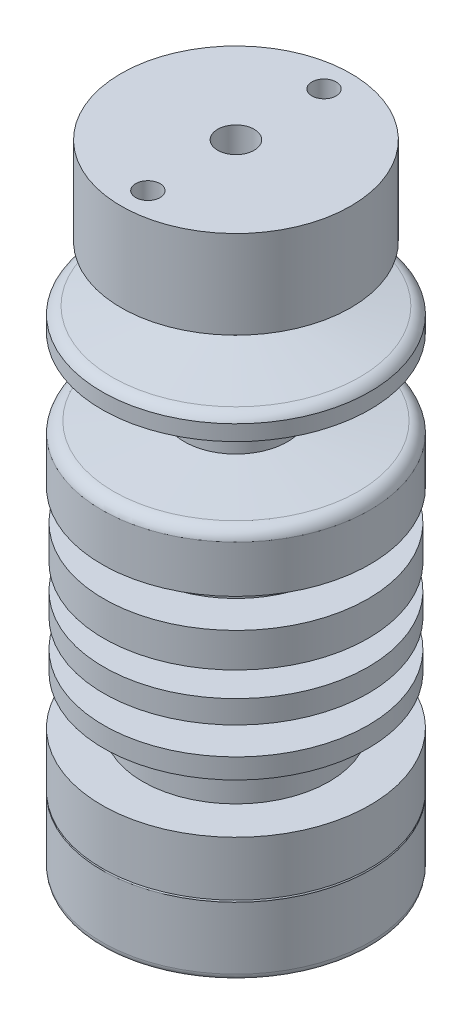
SolidWorks part; units mm, degrees
ref_plane "Alzado" through (0, 0, 0) normal (0, 0, 1) x (1, 0, 0)
ref_plane "Planta" through (0, 0, 0) normal (0, 1, 0) x (1, 0, 0)
ref_plane "Vista lateral" through (0, 0, 0) normal (1, 0, 0) x (0, 0, -1)
sketch "Croquis1" plane through (0, 0, 0) normal (0, 0, 1) x (1, 0, 0)
  line L0 (0, 0) -> (0, 43.0446) construction
  line L1 (0, 43.0446) -> (0, -121.9554) construction
  line L2 (0, 43.0446) -> (30, 43.0446)
  line L3 (30, 43.0446) -> (30, 20.0446)
  line L4 (30, 20.0446) -> (12.9858, 20.0446)
  line L5 (12.9858, 20.0446) -> (12.9858, 10.4062)
  line L6 (13.718, 8.5125) -> (32.3097, 5.486)
  line L7 (35, 3.5416) -> (35, -0.4901)
  line L8 (13.4687, -0.4901) -> (35, -0.4901)
  line L9 (13.4687, -0.4901) -> (13.4687, -18.5388)
  line L10 (13.4687, -18.5388) -> (31.9792, -20.5132)
  line L11 (35, -23.2242) -> (35, -35.5011)
  line L12 (24.3347, -77.3577) -> (34.5383, -77.3577)
  line L13 (24.3347, -77.3577) -> (24.3347, -104.2217)
  line L14 (24.3347, -104.2217) -> (34.5383, -104.2217)
  line L15 (35, -104.6833) -> (35, -120.9509)
  line L16 (34.7378, -121.991) -> (0, -121.9554)
  line L17 (0, 43.0446) -> (0, -121.9554)
  line L18 (34.5383, -77.3577) -> (34.5383, -72.1328)
  line L19 (35, -35.5011) -> (24.3347, -35.5011)
  line L20 (24.3347, -35.5011) -> (24.3347, -43.5201)
  line L21 (34.5383, -72.1328) -> (24.3347, -72.1328)
  line L22 (24.3347, -64.9174) -> (34.5383, -64.9174)
  line L23 (34.5383, -64.9174) -> (34.5383, -58.9461)
  line L24 (34.5383, -58.9461) -> (24.3347, -58.9461)
  line L25 (24.3347, -52.4771) -> (34.5383, -52.4771)
  line L26 (34.5383, -52.4771) -> (34.5383, -43.5201)
  line L27 (34.5383, -43.5201) -> (24.3347, -43.5201)
  line L28 (24.3347, -64.9174) -> (24.3347, -72.1328)
  line L29 (24.3347, -52.4771) -> (24.3347, -58.9461)
  arc A2 (12.9858, 10.4062) -> (13.718, 8.5125) centre (15.8008, 10.4062) ccw
  arc A3 (32.3097, 5.486) -> (35, 3.5416) centre (31.7144, 1.829) cw
  arc A6 (31.9792, -20.5132) -> (35, -23.2242) centre (31.6114, -23.9615) cw
  arc A8 (34.5383, -104.2217) -> (35, -104.6833) centre (34.5383, -104.6833) cw
  arc A9 (35, -120.9509) -> (34.7378, -121.991) centre (32.8058, -120.9509) cw
  dimension "D1" = 165
  dimension "D2" = 23
  dimension "D3" = 35
  dimension "D4" = 35
  dimension "D5" = 35
revolve "Revolución3" add sketch "Croquis1" angle 360 about L17
sketch "Croquis5" plane through (0, -104.2217, 0) normal (0, 1, 0) x (1, 0, 0)
  circle A0 centre (0.0979, 0) radius 7.9375
  dimension "D1" = 15.875
extrude "Cortar-Extruir3" cut sketch "Croquis5" along normal blind 8 and the other way blind 27
ref_plane "Plano1" through (0, 0, 0) normal (1, 0, 0) x (0, 0, -1)
ref_plane "Plano2" through (0, 0, 0) normal (0, 0, 1) x (1, 0, 0)
sketch "Croquis9" plane through (0, 43.0446, 0) normal (0, 1, 0) x (1, 0, 0)
  line L0 (0, 0) -> (0, -23) construction
  line L1 (0, -38.5) -> (0, 38.5) construction
  line L2 (0, 0) -> (0, 23) construction
  circle A0 centre (0, 23) radius 3.175
  circle A1 centre (0, -23) radius 3.175
  dimension "D3" = 6.35
  dimension "D4" = 6.35
  dimension "D1" = 23
  dimension "D2" = 23
extrude "Cortar-Extruir5" cut sketch "Croquis9" against normal blind 18
sketch "Croquis10" plane through (0, 43.0446, 0) normal (0, 1, 0) x (1, 0, 0)
  circle A0 centre (0, 0) radius 4.765
  dimension "D1" = 9.53
extrude "Cortar-Extruir6" cut sketch "Croquis10" against normal blind 35
sketch "Croquis11" plane through (0, -104.2217, 0) normal (0, 1, 0) x (1, 0, 0)
  circle A0 centre (0, 0) radius 35
  dimension "D1" = 70
extrude "Saliente-Extruir1" add sketch "Croquis11" along normal blind 14.24
sketch "Croquis13" plane through (0, -104.2217, 0) normal (0, -1, 0) x (1, 0, 0)
  circle A0 centre (0, 0) radius 8.0354
extrude "Cortar-Extruir8" cut sketch "Croquis13" against normal blind 30.21
